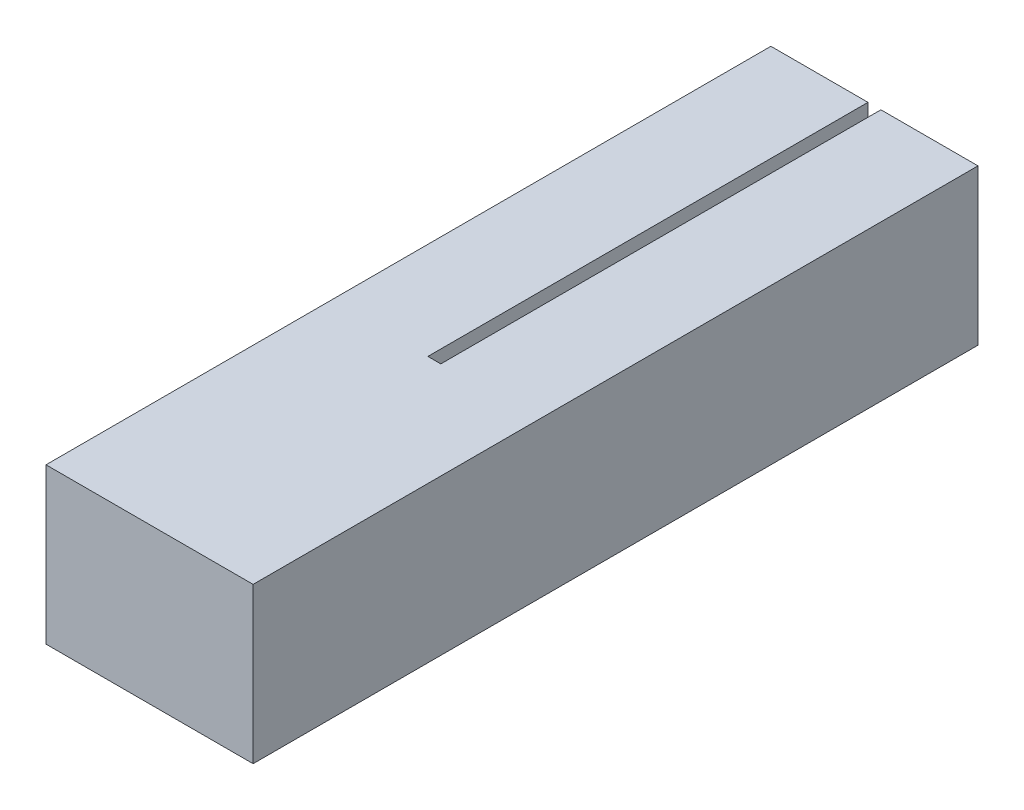
SolidWorks part; units mm, degrees
ref_plane "Front Plane" through (0, 0, 0) normal (0, 0, 1) x (1, 0, 0)
ref_plane "Top Plane" through (0, 0, 0) normal (0, 1, 0) x (1, 0, 0)
ref_plane "Right Plane" through (0, 0, 0) normal (1, 0, 0) x (0, 0, -1)
sketch "Sketch1" plane through (0, 0, 0) normal (0, 1, 0) x (1, 0, 0)
  line L1 (0, 0) -> (25.4, 0)
  line L2 (0, 0) -> (0, 88.9)
  line L3 (0, 88.9) -> (25.4, 88.9)
  line L4 (25.4, 0) -> (25.4, 88.9)
  dimension "D1" = 25.4
  dimension "D2" = 88.9
extrude "Boss-Extrude1" add sketch "Sketch1" along normal blind 19.05
sketch "Sketch2" plane through (0, 19.05, 0) normal (0, 1, 0) x (1, 0, 0)
  line L0 (25.4, 88.9) -> (0, 88.9) construction
  line L1 (11.9062, 88.9) -> (13.4938, 88.9)
  line L2 (11.9062, 88.9) -> (11.9063, 34.925)
  line L3 (11.9063, 34.925) -> (13.4938, 34.925)
  line L4 (13.4938, 88.9) -> (13.4938, 34.925)
  line L5 (0, 88.9) -> (0, 0) construction
  dimension "D1" = 53.975
  dimension "D2" = 1.5875
  dimension "D3" = 11.9062
extrude "Cut-Extrude1" cut sketch "Sketch2" against normal through all
